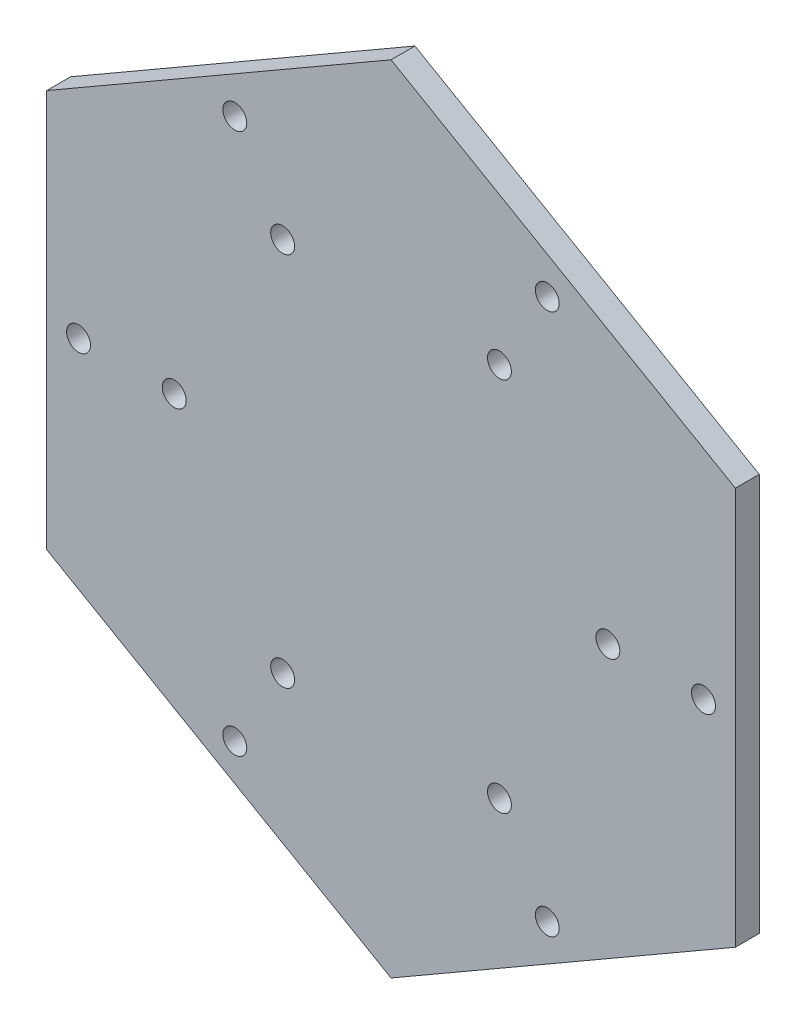
SolidWorks part; units mm, degrees
ref_plane "Front Plane" through (0, 0, 0) normal (0, 0, 1) x (1, 0, 0)
ref_plane "Top Plane" through (0, 0, 0) normal (0, 1, 0) x (1, 0, 0)
ref_plane "Right Plane" through (0, 0, 0) normal (1, 0, 0) x (0, 0, -1)
sketch "Sketch1" plane through (0, 0, 0) normal (0, 0, 1) x (1, 0, 0)
  line L1 (0, -49.8907) -> (43.2067, -24.9454)
  line L2 (43.2067, -24.9454) -> (43.2067, 24.9454)
  line L3 (43.2067, 24.9454) -> (0, 49.8907)
  line L4 (0, 49.8907) -> (-43.2067, 24.9454)
  line L5 (-43.2067, 24.9454) -> (-43.2067, -24.9454)
  line L6 (-43.2067, -24.9454) -> (0, -49.8907)
  circle A0 centre (0, 0) radius 43.2067 construction
extrude "Boss-Extrude1" add sketch "Sketch1" along normal blind 3
sketch "Sketch2" plane through (0, 0, 3) normal (0, 0, 1) x (1, 0, 0)
  line L0 (43.2067, -24.9454) -> (43.2067, 24.9454) construction
  circle A0 centre (27.2067, 0) radius 1.5
  circle A1 centre (39.2067, 0) radius 1.5
  circle A2 centre (13.6033, -23.5617) radius 1.5
  circle A3 centre (19.6033, -33.954) radius 1.5
  circle A4 centre (-13.6033, -23.5617) radius 1.5
  circle A5 centre (-19.6033, -33.954) radius 1.5
  circle A6 centre (-27.2067, 0) radius 1.5
  circle A7 centre (-39.2067, 0) radius 1.5
  circle A8 centre (-13.6033, 23.5617) radius 1.5
  circle A9 centre (-19.6033, 33.954) radius 1.5
  circle A10 centre (13.6033, 23.5617) radius 1.5
  circle A11 centre (19.6033, 33.954) radius 1.5
  dimension "D1" = 4
  dimension "D2" = 12
  dimension "D3" = 3
  dimension "D4" = 3
  dimension "D5" = 6
extrude "Cut-Extrude1" cut sketch "Sketch2" against normal blind 3
